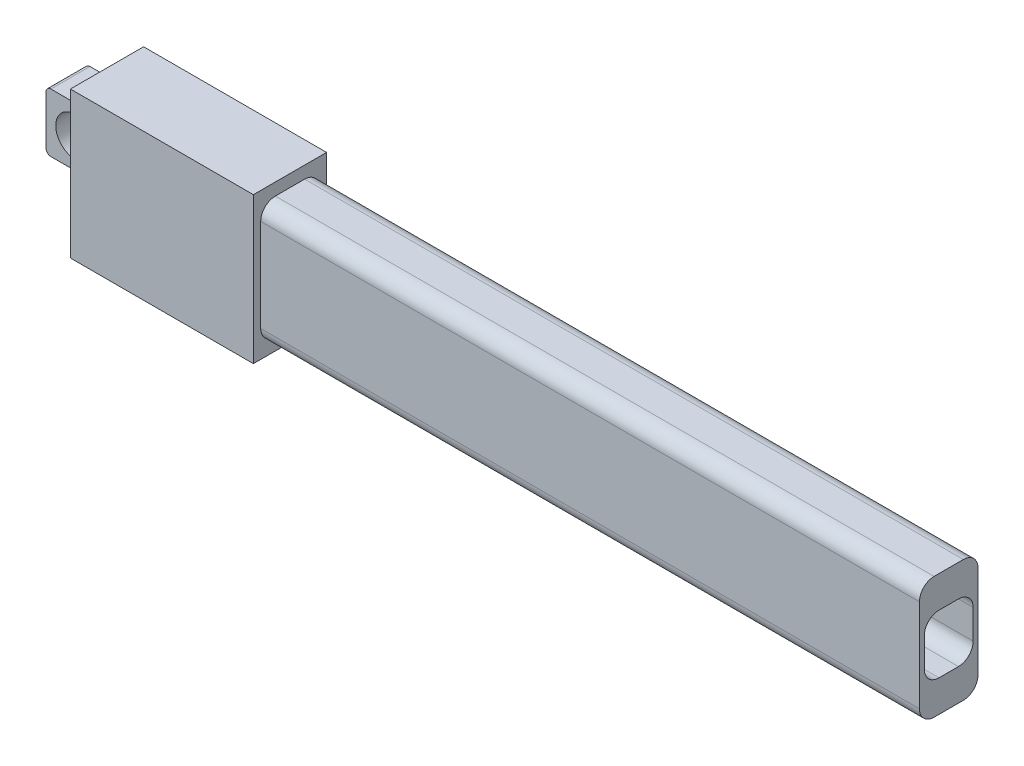
SolidWorks part; units mm, degrees
material "ABS PC"
ref_plane "Front" through (0, 0, 0) normal (0, 0, 1) x (1, 0, 0)
ref_plane "Top" through (0, 0, 0) normal (0, 1, 0) x (1, 0, 0)
ref_plane "Right" through (0, 0, 0) normal (1, 0, 0) x (0, 0, -1)
sketch "Croquis1" plane through (0, 0, 0) normal (0, 0, 1) x (1, 0, 0)
  line L2 (-18.75, -15) -> (18.75, -15)
  line L3 (-18.75, -15) -> (-18.75, 15)
  line L4 (-18.75, 15) -> (18.75, 15)
  line L5 (18.75, -15) -> (18.75, 15)
  line L6 (-18.75, -15) -> (18.75, 15) construction
  line L7 (-18.75, 15) -> (18.75, -15) construction
  point P1 (0, 0)
  dimension "D1" = 37.5
  dimension "D2" = 30
extrude "Saliente-Extruir1" add sketch "Croquis1" along normal blind 15
sketch "Croquis2" plane through (0, 0, 0) normal (0, 0, 1) x (1, 0, 0)
  line L0 (-18.75, 15) -> (-18.75, -15) construction
  line L1 (-18.75, 6) -> (-29.75, 6)
  line L2 (-18.75, 6) -> (-18.75, -6)
  line L3 (-18.75, -6) -> (-29.75, -6)
  line L4 (-30.75, 5) -> (-30.75, -5)
  line L5 (0, 0) -> (-15.2309, 0) construction
  line L6 (-30.75, 0) -> (-18.75, 0) construction
  line L12 (0, 0) -> (0, -15) construction
  line L13 (-18.75, -15) -> (18.75, -15) construction
  circle A0 centre (-24.75, 0) radius 4
  arc A1 (-29.75, -6) -> (-30.75, -5) centre (-29.75, -5) cw
  arc A2 (-29.75, 6) -> (-30.75, 5) centre (-29.75, 5) ccw
  point P16 (-30.75, -6)
  point P19 (-30.75, 6)
  dimension "D2" = 8
  dimension "D4" = 1
  dimension "D1" = 12
  dimension "D3" = 12
extrude "Saliente-Extruir2" add sketch "Croquis2" along normal blind 8
sketch "Croquis3" plane through (18.75, 0, 0) normal (1, 0, 0) x (0, 0, -1)
  line L0 (0, 0) -> (-15, 0) construction
  line L1 (-15, -15) -> (-15, 15) construction
  line L2 (0, -15) -> (0, 15) construction
  line L3 (-10.5, -12.5) -> (-4.5, -12.5)
  line L4 (-13.5, -9.5) -> (-13.5, 9.5)
  line L5 (-10.5, 12.5) -> (-4.5, 12.5)
  line L6 (-1.5, -9.5) -> (-1.5, 9.5)
  line L7 (-13.5, -12.5) -> (-1.5, 12.5) construction
  line L8 (-13.5, 12.5) -> (-1.5, -12.5) construction
  arc A0 (-10.5, -12.5) -> (-13.5, -9.5) centre (-10.5, -9.5) cw
  arc A1 (-4.5, -12.5) -> (-1.5, -9.5) centre (-4.5, -9.5) ccw
  arc A2 (-4.5, 12.5) -> (-1.5, 9.5) centre (-4.5, 9.5) cw
  arc A3 (-13.5, 9.5) -> (-10.5, 12.5) centre (-10.5, 9.5) cw
  point P5 (-7.5, 0)
  dimension "D3" = 3
  dimension "D1" = 1.5
  dimension "D2" = 25
sketch "Croquis4" plane through (0, 0, 15) normal (0, 0, 1) x (1, 0, 0)
  line L0 (-24.75, 0) -> (62.75, 0) construction
  dimension "D1" = 87.5
extrude "Saliente-Extruir3" add sketch "Croquis3" along normal blind 35
ref_plane "Plano1" through (0, 0, 7.5) normal (0, 0, 1) x (1, 0, 0)
sketch "Croquis5" plane through (0, 0, 7.5) normal (0, 0, 1) x (1, 0, 0)
  line L14 (-24.75, 0) -> (62.75, 0) construction
  line L15 (53.75, 6) -> (71.75, 6)
  line L16 (53.75, 9.5) -> (53.75, -9.5) construction
  line L17 (71.75, 6) -> (71.75, -6)
  line L18 (71.75, -6) -> (53.75, -6)
  line L19 (53.75, -6) -> (53.75, 6)
  circle A1 centre (62.75, 0) radius 4.5
  dimension "D1" = 12
  dimension "D2" = 6
  dimension "9" = 9
  dimension "D3" = 18
extrude "Saliente-Extruir4" add sketch "Croquis5" along normal mid plane 10
sketch "Croquis6" plane through (71.75, 0, 0) normal (1, 0, 0) x (0, 0, -1)
  line L0 (-11.5, 6) -> (-11.5, -6)
  line L1 (-12.5, 6) -> (-2.5, 6) construction
  line L2 (-12.5, -6) -> (-2.5, -6) construction
  line L3 (-3.5, 6) -> (-3.5, -6)
  line L4 (-12.5, 6) -> (-2.5, 6) construction
  line L5 (-12.5, -6) -> (-2.5, -6) construction
  line L6 (-12.5, -6) -> (-12.5, 6) construction
  line L7 (-2.5, -6) -> (-2.5, 6) construction
  line L8 (-3.5, -6) -> (-2.5, -6)
  line L9 (-11.5, 6) -> (-12.5, 6)
  line L12 (-2.5, -6) -> (-2.5, 6)
  line L13 (-2.5, 6) -> (-12.5, 6)
  line L14 (-12.5, 6) -> (-12.5, -6)
  line L15 (-12.5, -6) -> (-2.5, -6)
  line L16 (-2.5, -6) -> (-2.5, 6)
  line L17 (-2.5, 6) -> (-3.5, 6)
  line L18 (-12.5, 6) -> (-12.5, -6)
  line L19 (-12.5, -6) -> (-11.5, -6)
  dimension "D1" = 1
  dimension "D2" = 1
  dimension "D3" = 0
extrude "Cortar-Extruir2" cut sketch "Croquis6" against normal blind 14
fillet "Redondeo1" [suppressed] radius 3
fillet "Redondeo2" [suppressed] radius 3
sketch "Croquis7" plane through (0, 0, 15) normal (0, 0, 1) x (1, 0, 0)
  line L1 (53.75, 11.9051) -> (112.4881, 11.9051)
  line L2 (53.75, 11.9051) -> (53.75, -24.3061)
  line L3 (53.75, -24.3061) -> (112.4881, -24.3061)
  line L4 (112.4881, 11.9051) -> (112.4881, -24.3061)
  line L6 (53.75, 9.5) -> (53.75, -9.5) construction
extrude "Cortar-Extruir4" cut sketch "Croquis7" against normal through all
sketch "Croquis8" plane through (53.75, 0, 0) normal (1, 0, 0) x (0, 0, -1)
  line L0 (-13.5, 0) -> (-1.5, 0) construction
  line L1 (-13.5, 9.5) -> (-13.5, -9.5) construction
  line L2 (-1.5, -9.5) -> (-1.5, 9.5) construction
  line L4 (-9.5, -6) -> (-5.5, -6)
  line L5 (-12.5, -3) -> (-12.5, 3)
  line L6 (-9.5, 6) -> (-5.5, 6)
  line L7 (-2.5, -3) -> (-2.5, 3)
  line L8 (-12.5, -6) -> (-2.5, 6) construction
  line L9 (-12.5, 6) -> (-2.5, -6) construction
  arc A0 (-5.5, -6) -> (-2.5, -3) centre (-5.5, -3) ccw
  arc A1 (-9.5, -6) -> (-12.5, -3) centre (-9.5, -3) cw
  arc A2 (-12.5, 3) -> (-9.5, 6) centre (-9.5, 3) cw
  arc A3 (-5.5, 6) -> (-2.5, 3) centre (-5.5, 3) cw
  point P6 (-7.5, 0)
  dimension "D3" = 3
  dimension "D1" = 10
  dimension "D2" = 12
extrude "Cortar-Extruir5" cut sketch "Croquis8" against normal blind 30
sketch "Croquis9" plane through (0, 0, 15) normal (0, 0, 1) x (1, 0, 0)
  line L1 (-17, -13.5) -> (17, -13.5) construction
  line L2 (-17, -13.5) -> (-17, 13.5) construction
  line L3 (-17, 13.5) -> (17, 13.5) construction
  line L4 (17, -13.5) -> (17, 13.5) construction
  line L5 (-17, -13.5) -> (17, 13.5) construction
  line L6 (-17, 13.5) -> (17, -13.5) construction
  circle A0 centre (-17, 13.5) radius 0.75
  circle A1 centre (17, 13.5) radius 0.75
  circle A2 centre (17, -13.5) radius 0.75
  circle A3 centre (-17, -13.5) radius 0.75
  point P8 (0, 0)
  dimension "D1" = 1.5
  dimension "D2" = 34
  dimension "D3" = 27
extrude "Cortar-Extruir6" [suppressed] cut sketch "Croquis9" against normal blind 2
sketch "Croquis10" plane through (53.75, 0, 0) normal (1, 0, 0) x (0, 0, -1)
  line L0 (-2.5, -3) -> (-2.5, 3) construction
  line L1 (-9.5, -6) -> (-5.5, -6) construction
  line L2 (-12.5, 3) -> (-12.5, -3) construction
  line L3 (-5.5, 6) -> (-9.5, 6) construction
  line L4 (-13.5, 9.5) -> (-13.5, -9.5)
  line L5 (-10.5, -12.5) -> (-4.5, -12.5)
  line L6 (-1.5, -9.5) -> (-1.5, 9.5)
  line L7 (-4.5, 12.5) -> (-10.5, 12.5)
  line L8 (-13.5, 9.5) -> (-13.5, -9.5)
  line L9 (-10.5, -12.5) -> (-4.5, -12.5)
  line L10 (-1.5, -9.5) -> (-1.5, 9.5)
  line L11 (-4.5, 12.5) -> (-10.5, 12.5)
  line L12 (-2.5, -3) -> (-2.5, 3)
  line L13 (-9.5, -6) -> (-5.5, -6)
  line L14 (-12.5, 3) -> (-12.5, -3)
  line L15 (-5.5, 6) -> (-9.5, 6)
  arc A0 (-5.5, -6) -> (-2.5, -3) centre (-5.5, -3) ccw construction
  arc A1 (-12.5, -3) -> (-9.5, -6) centre (-9.5, -3) ccw construction
  arc A2 (-9.5, 6) -> (-12.5, 3) centre (-9.5, 3) ccw construction
  arc A3 (-2.5, 3) -> (-5.5, 6) centre (-5.5, 3) ccw construction
  arc A4 (-10.5, 12.5) -> (-13.5, 9.5) centre (-10.5, 9.5) ccw
  arc A5 (-13.5, -9.5) -> (-10.5, -12.5) centre (-10.5, -9.5) ccw
  arc A6 (-4.5, -12.5) -> (-1.5, -9.5) centre (-4.5, -9.5) ccw
  arc A7 (-1.5, 9.5) -> (-4.5, 12.5) centre (-4.5, 9.5) ccw
  arc A8 (-10.5, 12.5) -> (-13.5, 9.5) centre (-10.5, 9.5) ccw
  arc A9 (-13.5, -9.5) -> (-10.5, -12.5) centre (-10.5, -9.5) ccw
  arc A10 (-4.5, -12.5) -> (-1.5, -9.5) centre (-4.5, -9.5) ccw
  arc A11 (-1.5, 9.5) -> (-4.5, 12.5) centre (-4.5, 9.5) ccw
  arc A12 (-5.5, -6) -> (-2.5, -3) centre (-5.5, -3) ccw
  arc A13 (-12.5, -3) -> (-9.5, -6) centre (-9.5, -3) ccw
  arc A14 (-9.5, 6) -> (-12.5, 3) centre (-9.5, 3) ccw
  arc A15 (-2.5, 3) -> (-5.5, 6) centre (-5.5, 3) ccw
  dimension "D1" = 0
extrude "Saliente-Extruir5" add sketch "Croquis10" along normal blind 100
